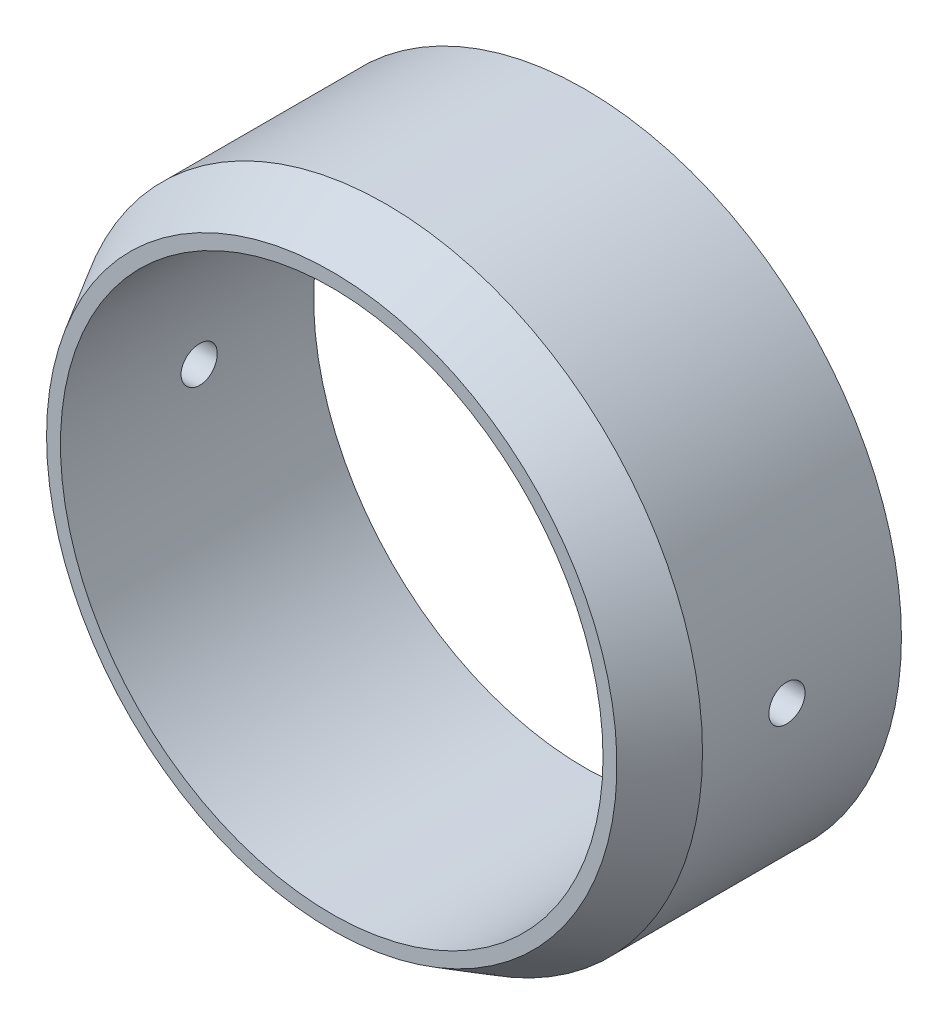
SolidWorks part; units mm, degrees
ref_plane "Front Plane" through (0, 0, 0) normal (0, 0, 1) x (1, 0, 0)
ref_plane "Top Plane" through (0, 0, 0) normal (0, 1, 0) x (1, 0, 0)
ref_plane "Right Plane" through (0, 0, 0) normal (1, 0, 0) x (0, 0, -1)
sketch "Sketch1" plane through (0, 0, 0) normal (0, 0, 1) x (1, 0, 0)
  circle A0 centre (0, 0) radius 44.45
  circle A1 centre (0, 0) radius 38.1
  dimension "D1" = 88.9
  dimension "D2" = 6.35
extrude "Boss-Extrude1" add sketch "Sketch1" along normal blind 35.56
chamfer "Chamfer1" distance 7.62 angle 30 1 edges at (44.45, 0, 35.56)
sketch "Sketch2" plane through (0, 0, 0) normal (1, 0, 0) x (0, 0, -1)
  line L0 (0, -44.45) -> (0, 44.45) construction
  circle A0 centre (-16.0782, 0) radius 2.54
  dimension "D1" = 5.08
  dimension "D2" = 16.0782
extrude "Cut-Extrude1" cut sketch "Sketch2" against normal through all both and the other way through all
